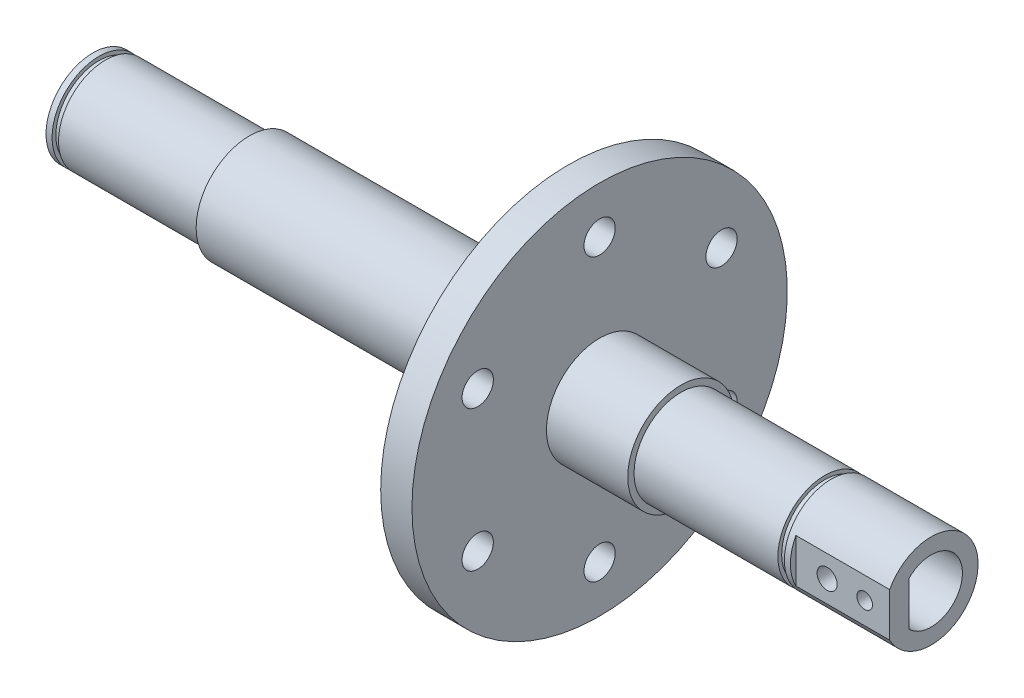
SolidWorks part; units mm, degrees
ref_plane "Front" through (0, 0, 0) normal (0, 0, 1) x (1, 0, 0)
ref_plane "Top" through (0, 0, 0) normal (0, 1, 0) x (1, 0, 0)
ref_plane "Right" through (0, 0, 0) normal (1, 0, 0) x (0, 0, -1)
sketch "草图1" plane through (0, 0, 0) normal (0, 0, 1) x (1, 0, 0)
  line L0 (0, 0) -> (134, 0)
  line L1 (94, 7.5) -> (134, 7.5)
  line L2 (81, 8.5) -> (94, 8.5)
  line L3 (81, 8.5) -> (81, 30)
  line L4 (81, 30) -> (76, 30)
  line L5 (76, 30) -> (76, 8.5)
  line L6 (76, 8.5) -> (25, 8.5)
  line L7 (25, 8.5) -> (25, 7.5)
  line L8 (25, 7.5) -> (0, 7.5)
  line L9 (0, 7.5) -> (0, 0)
  line L10 (94, 8.5) -> (94, 7.5)
  line L11 (134, 7.5) -> (134, 0)
  dimension "D1" = 134
  dimension "D2" = 40
  dimension "D3" = 25
  dimension "D4" = 13
  dimension "D5" = 7.5
  dimension "D6" = 8.5
  dimension "D7" = 7.5
  dimension "D8" = 30
  dimension "D9" = 5
revolve "旋转1" add sketch "草图1" angle 360 about L0
sketch "草图2" plane through (76, 0, 0) normal (-1, 0, 0) x (0, 0, 1)
  circle A0 centre (0, 0) radius 22.5 construction
  circle A1 centre (0, 22.5) radius 2.5
  circle A2 centre (19.4856, 11.25) radius 2.5
  circle A3 centre (19.4856, -11.25) radius 2.5
  circle A4 centre (0, -22.5) radius 2.5
  circle A5 centre (-19.4856, -11.25) radius 2.5
  circle A6 centre (-19.4856, 11.25) radius 2.5
  point P17 (0, 0)
  dimension "D1" = 45
  dimension "D2" = 5
  dimension "D3" = 6
extrude "切除-拉伸1" cut sketch "草图2" against normal through all
sketch "草图3" plane through (134, 0, 0) normal (1, 0, 0) x (0, 0, -1)
  line L0 (-3.5707, 3.5) -> (-3.5707, -3.5)
  arc A0 (-3.5707, -3.5) -> (-3.5707, 3.5) centre (0, 0) ccw
  dimension "D1" = 10
  dimension "D2" = 7
extrude "切除-拉伸2" cut sketch "草图3" against normal blind 14
sketch "草图4" plane through (134, 0, 0) normal (1, 0, 0) x (0, 0, -1)
  line L0 (-6.6332, 3.5) -> (-6.6332, -3.5)
  circle A0 centre (0, 0) radius 7.5 construction
  circle A1 centre (0, 0) radius 7.5 construction
  arc A2 (-6.6332, 3.5) -> (-6.6332, -3.5) centre (0, 0) ccw
  dimension "D1" = 7
extrude "切除-拉伸3" cut sketch "草图4" against normal blind 15
sketch "草图5" plane through (0, 0, 6.6332) normal (0, 0, 1) x (1, 0, 0)
  line L0 (134, -3.5) -> (134, 3.5) construction
  circle A0 centre (130, 0) radius 1.5 construction
  circle A1 centre (124, 0) radius 1.6
  dimension "D1" = 3
  dimension "D4" = 3.2
  dimension "D2" = 6
  dimension "D3" = 4
extrude "切除-拉伸4" cut sketch "草图5" against normal through all
sketch "草图6" plane through (0, 0, 6.6332) normal (0, 0, 1) x (1, 0, 0)
  line L0 (134, -3.5) -> (134, 3.5) construction
  circle A0 centre (130, 0) radius 1.5 construction
  dimension "D1" = 3
  dimension "D2" = 4
hole_wizard "M3 螺纹孔1" positions "3D草图1" profile "草图7" tap size "M3" standard "GB"
sketch3d "3D草图1"
  point P0 (130, 0, 6.6332)
sketch "草图7" plane through (130, 0, 6.6332) normal (1, 0, 0) x (0, -1, 0)
  line L0 (0, 0) -> (0, 4.7511)
  line L1 (0, 4.7511) -> (1.25, 4)
  line L2 (1.25, 4) -> (1.25, 0)
  line L5 (1.25, 0) -> (0, 0)
  line L10 (0, 4.7511) -> (-1.25, 4) construction
  line L11 (0, -6.35) -> (0, 107.95) construction
  dimension "螺纹孔钻头直径" = 2.5
  dimension "螺纹孔钻头深度" = 4
  dimension "导头角度" = 118
cosmetic thread "孔螺蚊线1" parameters "D1"=3, "D2"=3
ref_plane "基准面1" through (2, 0, 0) normal (-1, 0, 0) x (0, 0, 1)
sketch "草图8" plane through (2, 0, 0) normal (-1, 0, 0) x (0, 0, 1)
  circle A0 centre (0, 0) radius 6.9
  circle A1 centre (0, 0) radius 7.5 construction
  circle A2 centre (0, 0) radius 7.5
  dimension "D1" = 13.8
extrude "切除-拉伸5" cut sketch "草图8" along normal blind 1.03
ref_plane "基准面2" through (117, 0, 0) normal (1, 0, 0) x (0, 0, -1)
sketch "草图9" plane through (117, 0, 0) normal (1, 0, 0) x (0, 0, -1)
  circle A0 centre (0, 0) radius 7.5 construction
  circle A1 centre (0, 0) radius 7.5
  circle A2 centre (0, 0) radius 6.9
  dimension "D1" = 13.8
extrude "切除-拉伸6" cut sketch "草图9" along normal blind 1.03
